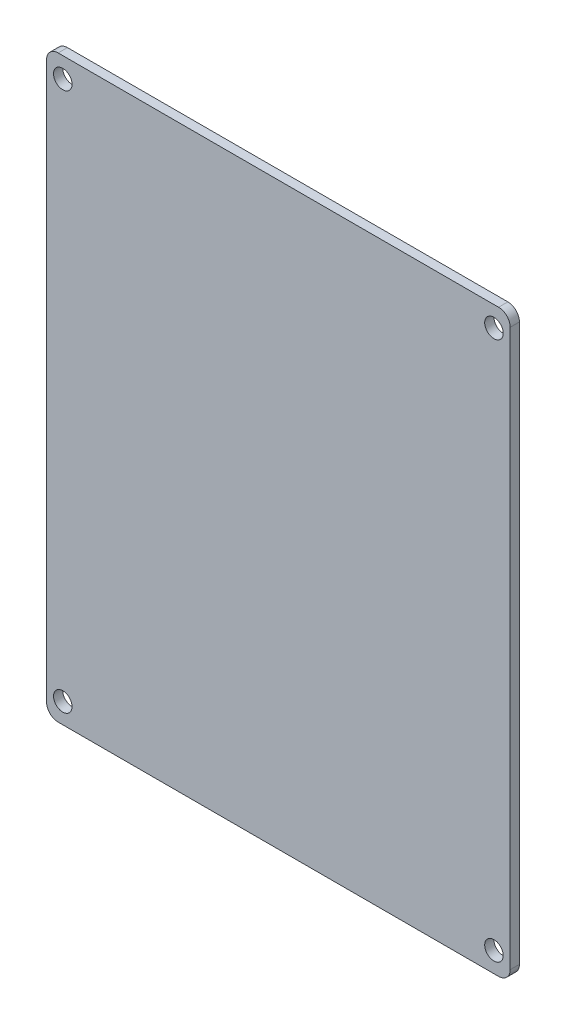
SolidWorks part; units mm, degrees
ref_plane "前视基准面" through (0, 0, 0) normal (0, 0, 1) x (1, 0, 0)
ref_plane "上视基准面" through (0, 0, 0) normal (0, 1, 0) x (1, 0, 0)
ref_plane "右视基准面" through (0, 0, 0) normal (1, 0, 0) x (0, 0, -1)
sketch "草图1" plane through (0, 0, 0) normal (0, 0, 1) x (1, 0, 0)
  line L0 (0, -0.88) -> (0, 0.88) construction
  line L1 (-40, -50) -> (40, -50)
  line L2 (-40, -50) -> (-40, 50)
  line L3 (-40, 50) -> (40, 50)
  line L4 (40, -50) -> (40, 50)
  line L5 (-40, -50) -> (40, 50) construction
  line L6 (-40, 50) -> (40, -50) construction
  line L7 (0.88, 0) -> (-0.88, 0) construction
  circle A0 centre (-37.2, 46.5) radius 1.6
  circle A1 centre (37.2, 46.5) radius 1.6
  circle A2 centre (37.2, -46.5) radius 1.6
  circle A3 centre (-37.2, -46.5) radius 1.6
  point P0 (0, 0)
  dimension "D4" = 3.2
  dimension "D1" = 80
  dimension "D2" = 100
  dimension "D3" = 93
extrude "凸台-拉伸1" add sketch "草图1" along normal blind 1.6
fillet "圆角1" radius 2 4 edges at (-40, 50, 0.8) (-40, -50, 0.8) (40, -50, 0.8) (40, 50, 0.8)
